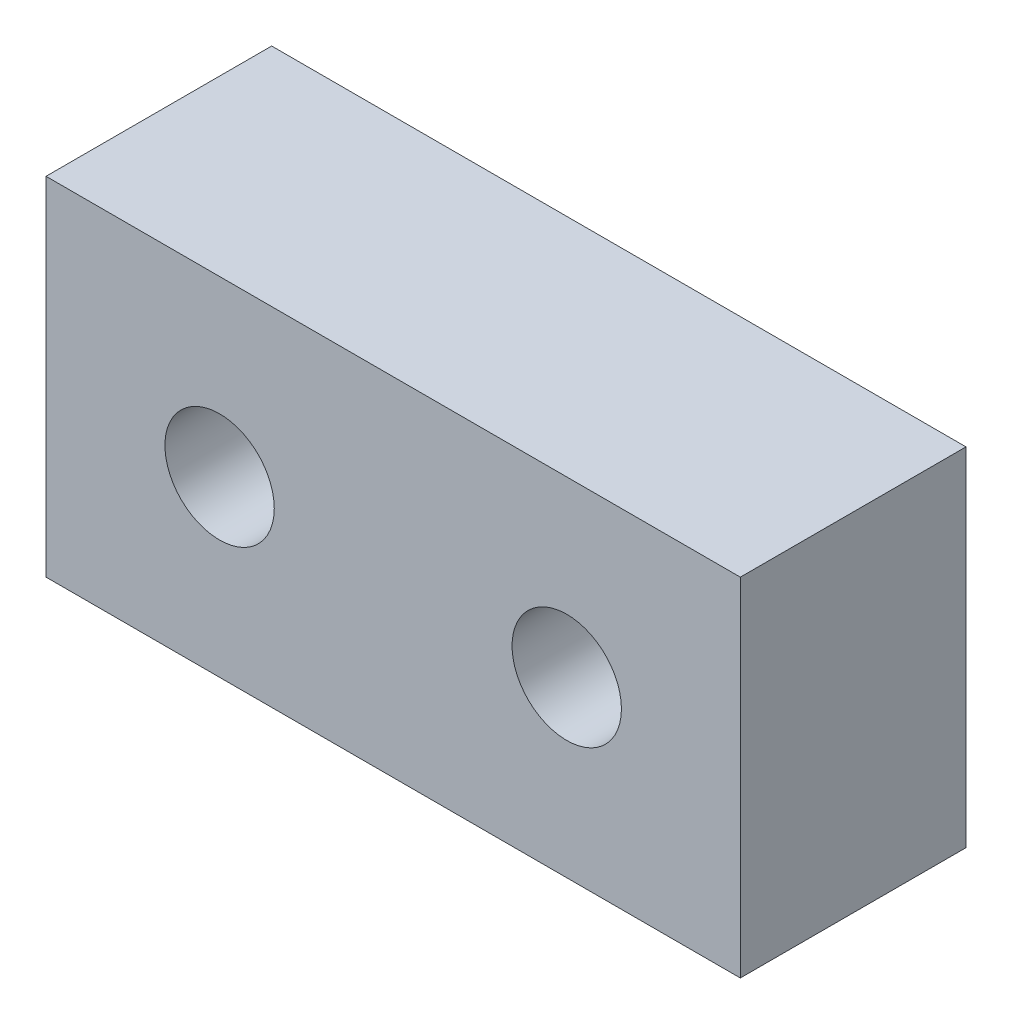
SolidWorks part; units mm, degrees
ref_plane "前视基准面" through (0, 0, 0) normal (0, 0, 1) x (1, 0, 0)
ref_plane "上视基准面" through (0, 0, 0) normal (0, 1, 0) x (1, 0, 0)
ref_plane "右视基准面" through (0, 0, 0) normal (1, 0, 0) x (0, 0, -1)
other "Configuration Table"
sketch "草图1" plane through (0, 0, 0) normal (0, 0, 1) x (1, 0, 0)
  line L1 (0, 0) -> (20, 0)
  line L2 (0, 0) -> (0, -10)
  line L3 (0, -10) -> (20, -10)
  line L4 (20, 0) -> (20, -10)
  dimension "D1" = 10
  dimension "D2" = 20
extrude "凸台-拉伸1" add sketch "草图1" along normal blind 6.5
sketch "草图2" plane through (0, 0, 6.5) normal (0, 0, 1) x (1, 0, 0)
  line L0 (10, 0) -> (10, -10) construction
  line L1 (20, 0) -> (0, 0) construction
  line L2 (0, -10) -> (20, -10) construction
  circle A0 centre (5, -5) radius 1.575
  circle A1 centre (15, -5) radius 1.575
  dimension "D1" = 3.15
  dimension "D2" = 5
  dimension "D3" = 5
extrude "切除-拉伸1" cut sketch "草图2" against normal through all
